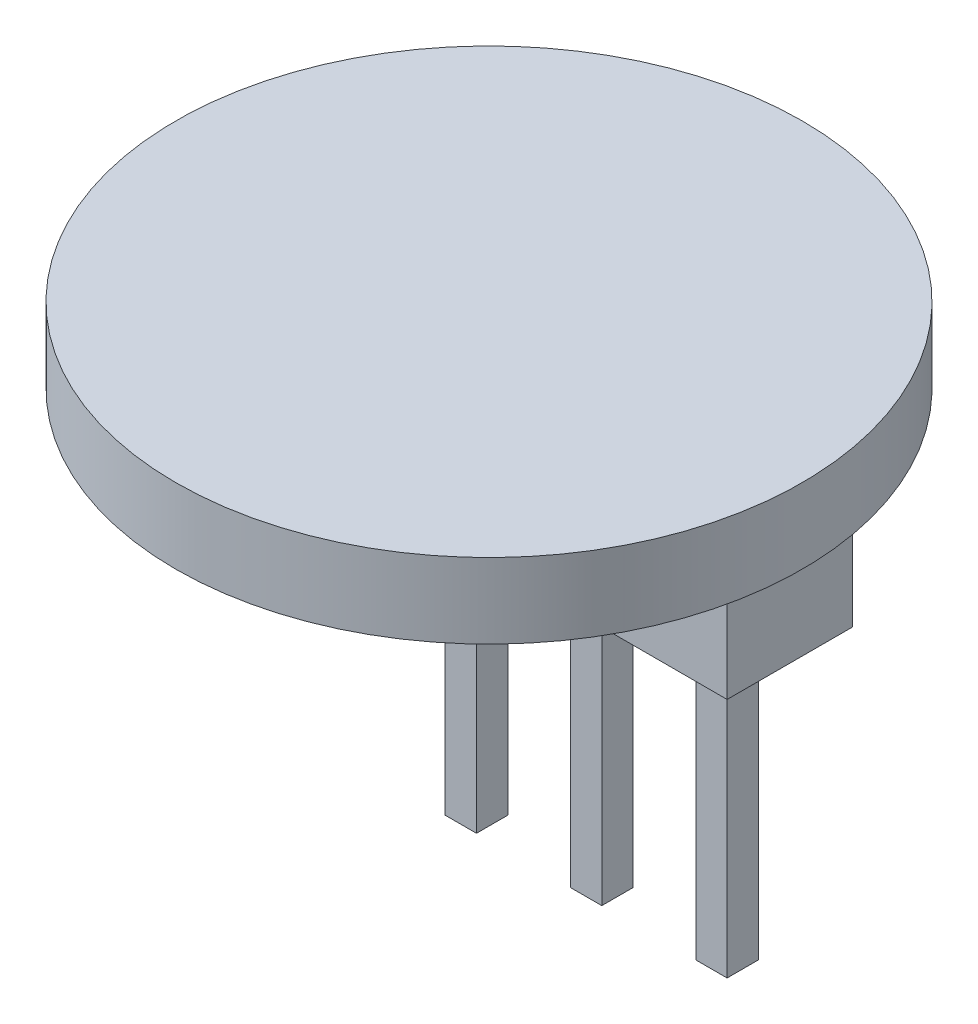
SolidWorks part; units mm, degrees
ref_plane "Front Plane" through (0, 0, 0) normal (0, 0, 1) x (1, 0, 0)
ref_plane "Top Plane" through (0, 0, 0) normal (0, 1, 0) x (1, 0, 0)
ref_plane "Right Plane" through (0, 0, 0) normal (1, 0, 0) x (0, 0, -1)
sketch "Sketch1" plane through (0, 0, 0) normal (0, 1, 0) x (1, 0, 0)
  circle A0 centre (0, 0) radius 6.35
  dimension "D1" = 12.7
extrude "Boss-Extrude1" add sketch "Sketch1" against normal blind 1.52
sketch "Sketch2" plane through (0, -1.52, 0) normal (0, -1, 0) x (1, 0, 0)
  line L1 (3.81, -3.556) -> (-3.81, -3.556)
  line L2 (3.81, -3.556) -> (3.81, -1.016)
  line L3 (3.81, -1.016) -> (-3.81, -1.016)
  line L4 (-3.81, -3.556) -> (-3.81, -1.016)
  line L5 (3.81, -3.556) -> (-3.81, -1.016) construction
  line L6 (3.81, -1.016) -> (-3.81, -3.556) construction
  point P0 (0, -2.286)
  dimension "D1" = 7.62
  dimension "D2" = 2.54
  dimension "D3" = 1.016
extrude "Boss-Extrude2" add sketch "Sketch2" along normal blind 4.064
sketch "Sketch3" plane through (0, -5.584, 0) normal (0, -1, 0) x (1, 0, 0)
  line L0 (-3.81, -2.286) -> (3.81, -2.286) construction
  line L1 (-3.81, -1.016) -> (-3.81, -3.556) construction
  line L2 (3.81, -3.556) -> (3.81, -1.016) construction
  line L3 (-0.3175, -1.9685) -> (0.3175, -1.9685)
  line L4 (-2.8575, -2.6035) -> (-2.2225, -2.6035)
  line L5 (-2.8575, -2.6035) -> (-2.8575, -1.9685)
  line L6 (-2.8575, -1.9685) -> (-2.2225, -1.9685)
  line L7 (-2.2225, -2.6035) -> (-2.2225, -1.9685)
  line L8 (-2.8575, -2.6035) -> (-2.2225, -1.9685) construction
  line L9 (-2.8575, -1.9685) -> (-2.2225, -2.6035) construction
  line L10 (-0.3175, -2.6035) -> (0.3175, -2.6035)
  line L11 (-0.3175, -2.6035) -> (-0.3175, -1.9685)
  line L12 (0.3175, -2.6035) -> (0.3175, -1.9685)
  line L13 (2.2225, -1.9685) -> (2.8575, -1.9685)
  line L14 (2.2225, -2.6035) -> (2.8575, -2.6035)
  line L15 (2.2225, -2.6035) -> (2.2225, -1.9685)
  line L16 (2.8575, -2.6035) -> (2.8575, -1.9685)
  point P6 (-2.54, -2.286)
  point P11 (0, -2.286)
  dimension "D1" = 0.635
  dimension "D2" = 0.635
  dimension "D4" = 2.54
  dimension "D3" = 3
extrude "Boss-Extrude3" add sketch "Sketch3" along normal blind 5.842
